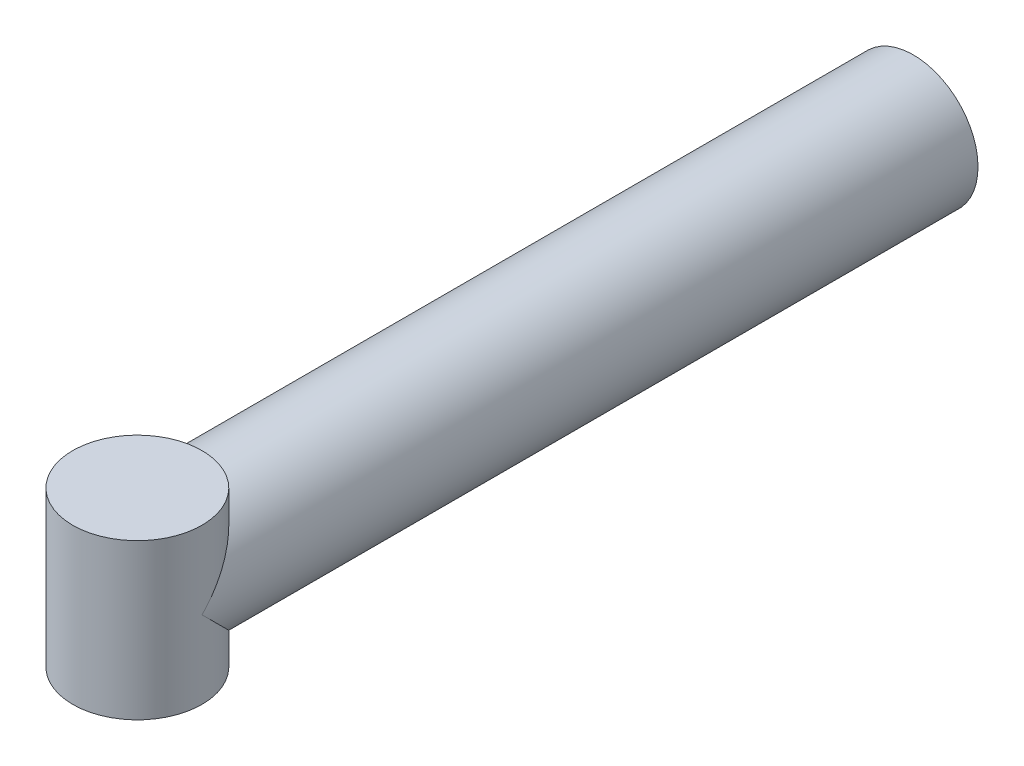
SolidWorks part; units mm, degrees
ref_plane "Alzado" through (0, 0, 0) normal (0, 0, 1) x (1, 0, 0)
ref_plane "Planta" through (0, 0, 0) normal (0, 1, 0) x (1, 0, 0)
ref_plane "Vista lateral" through (0, 0, 0) normal (1, 0, 0) x (0, 0, -1)
sketch "Croquis1" plane through (0, 0, 0) normal (0, 0, 1) x (1, 0, 0)
  circle A0 centre (0, 0) radius 6.25
  dimension "D1" = 12.5
extrude "Saliente-Extruir1" add sketch "Croquis1" along normal blind 75
sketch "Croquis2" plane through (0, 0, 0) normal (0, 1, 0) x (1, 0, 0)
  line L0 (-6.25, -75) -> (6.25, -75) construction
  circle A0 centre (0, -75) radius 6.25
extrude "Saliente-Extruir2" add sketch "Croquis2" along normal mid plane 15
